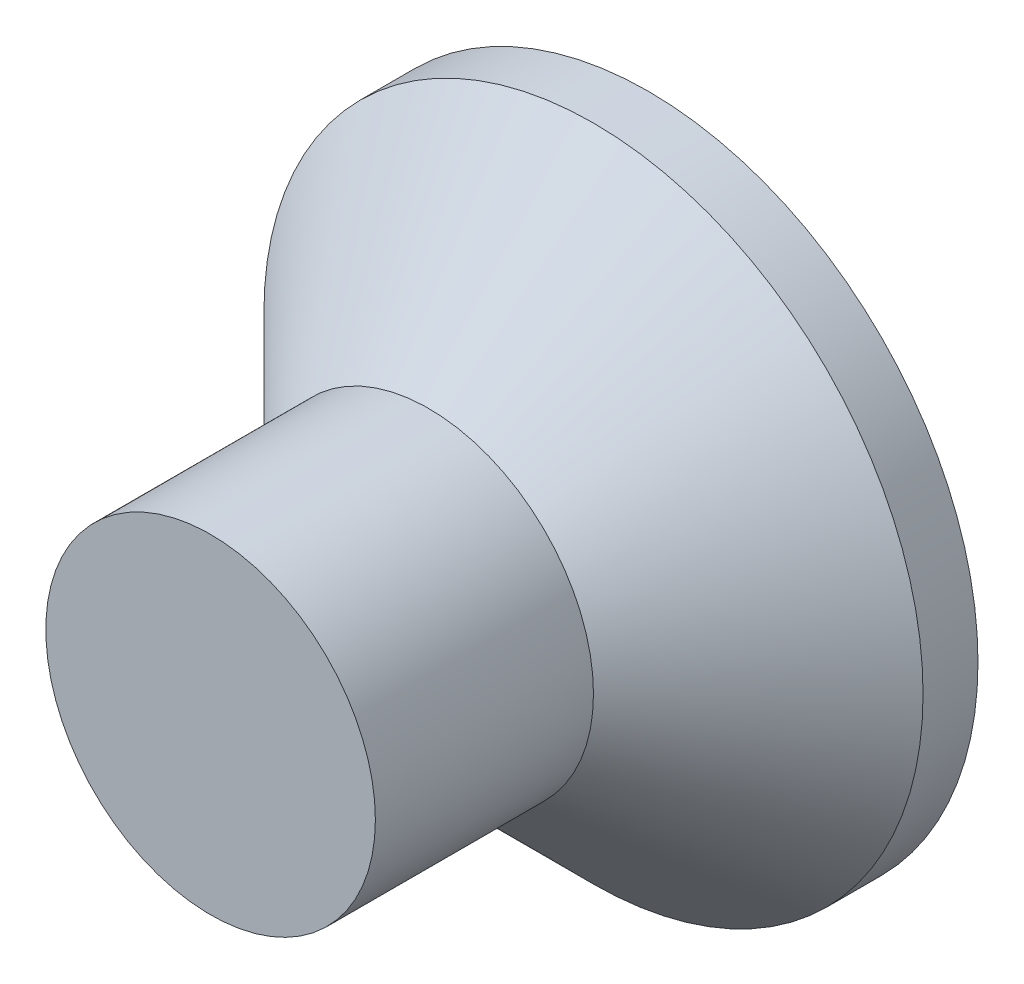
SolidWorks part; units mm, degrees
ref_plane "Front Plane" through (0, 0, 0) normal (0, 0, 1) x (1, 0, 0)
ref_plane "Top Plane" through (0, 0, 0) normal (0, 1, 0) x (1, 0, 0)
ref_plane "Right Plane" through (0, 0, 0) normal (1, 0, 0) x (0, 0, -1)
sketch "Sketch1" plane through (0, 0, 0) normal (0, 1, 0) x (1, 0, 0)
  line L0 (0, 0) -> (3, 0) construction
  line L1 (3, 0) -> (3, -0.5)
  line L2 (3, -0.5) -> (1.5, -2)
  line L3 (1.5, -2) -> (1.5, -3.9851)
  line L4 (1.5, -3.9851) -> (0, -3.9851)
  line L5 (0, 0) -> (0, -3.9851) construction
  line L6 (0, 0.6196) -> (-1.8126, 0.6196) construction
  line L7 (0, 0) -> (0, 0.6196) construction
  line L8 (0, -3.9851) -> (0, 0.6196)
  arc A0 (3, 0) -> (0, 0.6196) centre (0, -6.9529) ccw
  dimension "D1" = 3
  dimension "D2" = 0.5
  dimension "D3" = 45
  dimension "D4" = 1.5
revolve "Revolve1" add sketch "Sketch1" angle 360 about L8
ref_plane "Plane1" through (0, 0, -0.6196) normal (0, 0, 1) x (1, 0, 0)
sketch "Sketch2" plane through (0, 0, -0.6196) normal (0, 0, 1) x (1, 0, 0)
  line L1 (1.5, 0) -> (0.75, 1.299)
  line L2 (0.75, 1.299) -> (-0.75, 1.299)
  line L3 (-0.75, 1.299) -> (-1.5, 0)
  line L4 (-1.5, 0) -> (-0.75, -1.299)
  line L5 (-0.75, -1.299) -> (0.75, -1.299)
  line L6 (0.75, -1.299) -> (1.5, 0)
  circle A0 centre (0, 0) radius 1.299 construction
  dimension "D1" = 1.5
extrude "Cut-Extrude1" cut sketch "Sketch2" along normal blind 1
chamfer "Chamfer1" distance 0.3 angle 45 6 edges at (1.125, 0.6495, 0.3804) (0, 1.299, 0.3804) (-1.125, 0.6495, 0.3804) (-1.125, -0.6495, 0.3804) (0, -1.299, 0.3804) (1.125, -0.6495, 0.3804)
